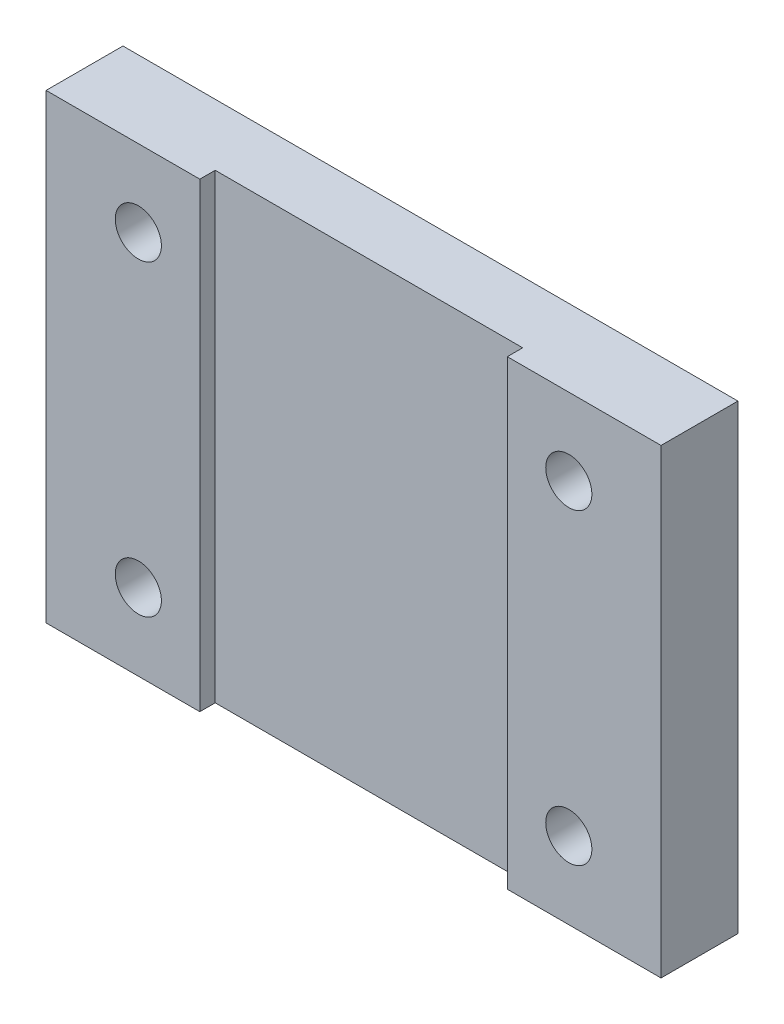
SolidWorks part; units mm, degrees
ref_plane "前视基准面" through (0, 0, 0) normal (0, 0, 1) x (1, 0, 0)
ref_plane "上视基准面" through (0, 0, 0) normal (0, 1, 0) x (1, 0, 0)
ref_plane "右视基准面" through (0, 0, 0) normal (1, 0, 0) x (0, 0, -1)
sketch "草图1" plane through (0, 0, 0) normal (0, 0, 1) x (1, 0, 0)
  line L1 (-20, 15) -> (20, 15)
  line L2 (-20, 15) -> (-20, -15)
  line L3 (-20, -15) -> (20, -15)
  line L4 (20, 15) -> (20, -15)
  line L5 (-20, 15) -> (20, -15) construction
  line L6 (-20, -15) -> (20, 15) construction
  point P0 (0, 0)
  dimension "D1" = 30
  dimension "D2" = 40
extrude "凸台-拉伸1" add sketch "草图1" along normal blind 5
sketch "草图2" plane through (0, 0, 0) normal (0, 0, -1) x (-1, 0, 0)
  line L0 (-20, -15) -> (-20, 15) construction
  circle A6 centre (14, 10) radius 1.5
  circle A7 centre (-14, 10) radius 1.5
  circle A8 centre (-14, -10) radius 1.5
  circle A9 centre (14, -10) radius 1.5
  dimension "D1" = 20
  dimension "D2" = 20
  dimension "D3" = 28
  dimension "D4" = 28
  dimension "D5" = 6
  dimension "D6" = 6
  dimension "D7" = 10
  dimension "D8" = 10
  dimension "D9" = 3
  dimension "D10" = 3
  dimension "D11" = 3
  dimension "D12" = 3
extrude "切除-拉伸1" cut sketch "草图2" against normal blind 10
sketch "草图3" plane through (0, 0, 5) normal (0, 0, 1) x (1, 0, 0)
  line L0 (-10, 15) -> (-10, -15)
  line L1 (20, 15) -> (-20, 15) construction
  line L2 (-20, -15) -> (20, -15) construction
  line L3 (-10, -15) -> (10, -15)
  line L4 (10, -15) -> (10, 15)
  line L5 (10, 15) -> (-10, 15)
  dimension "D1" = 20
  dimension "D2" = 10
extrude "切除-拉伸2" cut sketch "草图3" against normal blind 1
